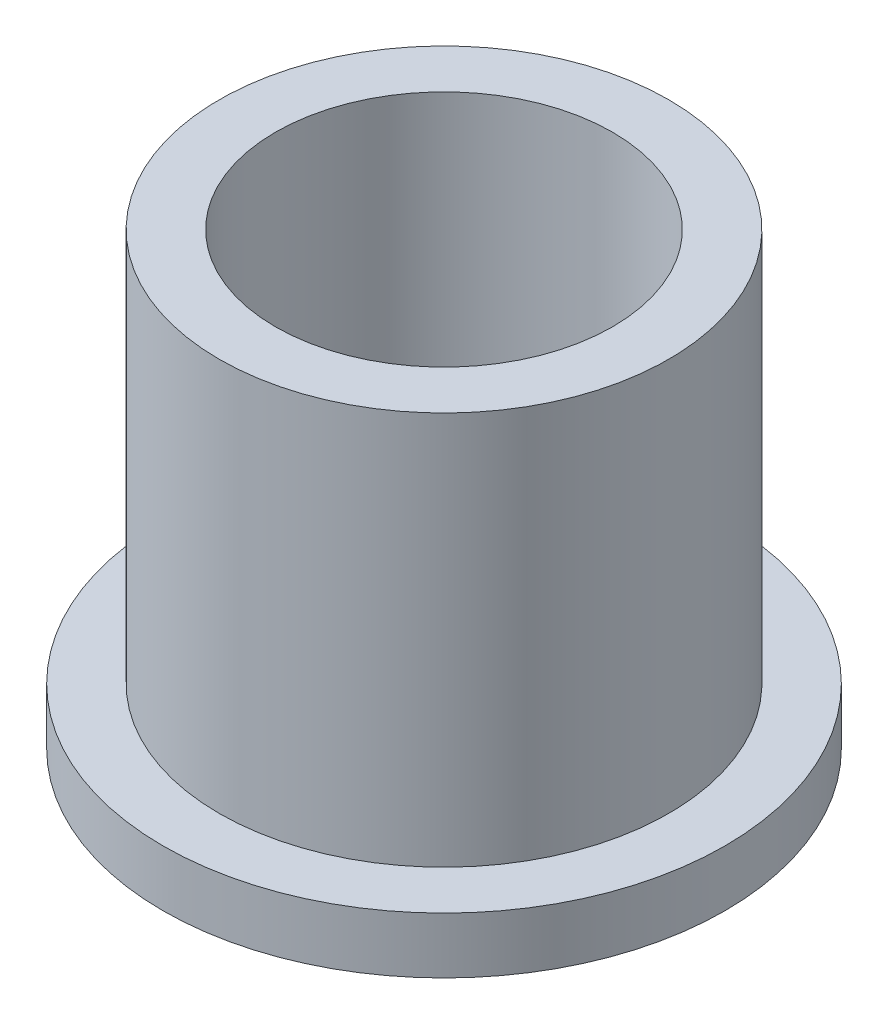
SolidWorks part; units mm, degrees
ref_plane "Front" through (0, 0, 0) normal (0, 0, 1) x (1, 0, 0)
ref_plane "Top" through (0, 0, 0) normal (0, 1, 0) x (1, 0, 0)
ref_plane "Right" through (0, 0, 0) normal (1, 0, 0) x (0, 0, -1)
sketch "Sketch1" plane through (0, 0, 0) normal (0, 1, 0) x (1, 0, 0)
  circle A0 centre (0, 0) radius 4.7625
  circle A1 centre (0, 0) radius 6.35
  circle A2 centre (0, 0) radius 7.9375
  dimension "ID" = 9.525
  dimension "OD" = 12.7
  dimension "FlangeOD" = 15.875
sketch "Sketch2" plane through (0, 0, 0) normal (0, 1, 0) x (1, 0, 0)
  circle A0 centre (0, 0) radius 4.7625 construction
  circle A1 centre (0, 0) radius 6.35 construction
  circle A2 centre (0, 0) radius 4.7625
  circle A3 centre (0, 0) radius 6.35
extrude "Boss-Extrude1" add sketch "Sketch2" along normal blind 12.7
sketch "Sketch3" plane through (0, 0, 0) normal (0, 1, 0) x (1, 0, 0)
  circle A0 centre (0, 0) radius 7.9375 construction
  circle A1 centre (0, 0) radius 6.35 construction
  circle A2 centre (0, 0) radius 7.9375
  circle A3 centre (0, 0) radius 6.35
extrude "Boss-Extrude2" add sketch "Sketch3" along normal blind 1.5875
